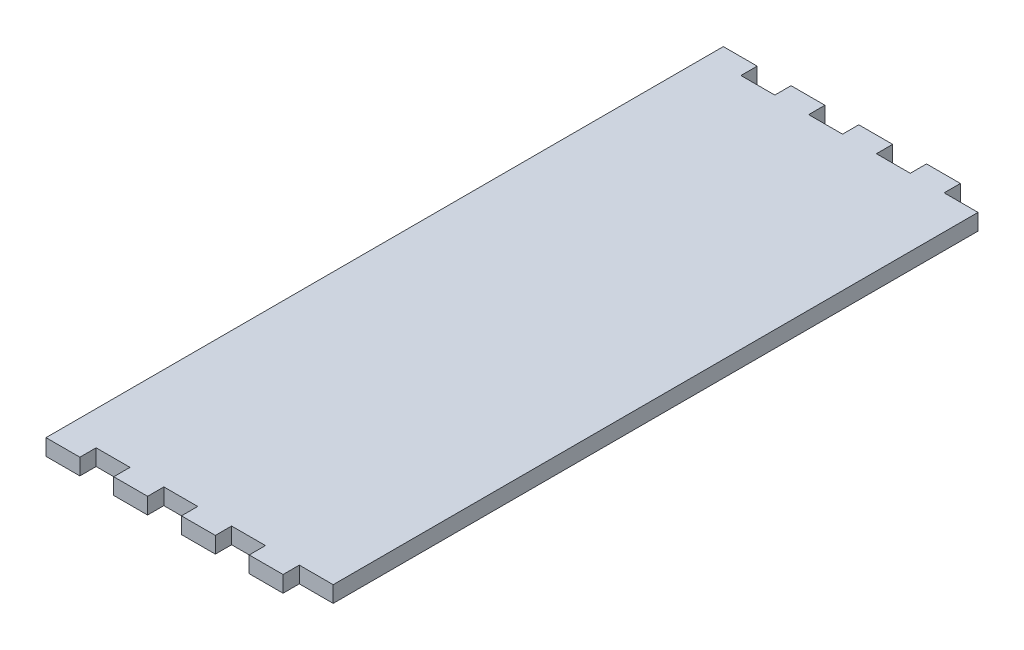
SolidWorks part; units mm, degrees
ref_plane "Front Plane" through (0, 0, 0) normal (0, 0, 1) x (1, 0, 0)
ref_plane "Top Plane" through (0, 0, 0) normal (0, 1, 0) x (1, 0, 0)
ref_plane "Right Plane" through (0, 0, 0) normal (1, 0, 0) x (0, 0, -1)
sketch "Sketch1" plane through (0, 0, 0) normal (0, 1, 0) x (1, 0, 0)
  line L0 (0, 0) -> (6.35, 0)
  line L1 (0, -127) -> (50.8, -127)
  line L2 (0, -127) -> (0, 0)
  line L3 (0, 0) -> (50.8, 0)
  line L4 (50.8, -127) -> (50.8, 0)
  line L5 (6.35, 0) -> (6.35, -3.048)
  line L6 (6.35, -3.048) -> (12.7, -3.048)
  line L7 (12.7, -3.048) -> (12.7, 0)
  line L8 (12.7, 0) -> (19.05, 0)
  line L9 (19.05, 0) -> (19.05, -3.048)
  line L10 (19.05, -3.048) -> (25.4, -3.048)
  line L11 (25.4, -3.048) -> (25.4, 0)
  line L12 (25.4, 0) -> (31.75, 0)
  line L13 (31.75, 0) -> (31.75, -3.048)
  line L14 (31.75, -3.048) -> (38.1, -3.048)
  line L15 (38.1, -3.048) -> (38.1, 0)
  line L16 (38.1, 0) -> (44.45, 0)
  line L17 (44.45, 0) -> (44.45, -3.048)
  line L18 (44.45, -3.048) -> (50.8, -3.048)
  line L19 (50.8, -3.048) -> (50.8, 0)
  line L20 (0, -63.5) -> (50.8, -63.5) construction
  line L21 (50.8, -123.952) -> (50.8, -127)
  line L22 (44.45, -123.952) -> (50.8, -123.952)
  line L23 (44.45, -127) -> (44.45, -123.952)
  line L24 (38.1, -127) -> (44.45, -127)
  line L25 (38.1, -123.952) -> (38.1, -127)
  line L26 (31.75, -123.952) -> (38.1, -123.952)
  line L27 (31.75, -127) -> (31.75, -123.952)
  line L28 (25.4, -127) -> (31.75, -127)
  line L29 (25.4, -123.952) -> (25.4, -127)
  line L30 (19.05, -123.952) -> (25.4, -123.952)
  line L31 (19.05, -127) -> (19.05, -123.952)
  line L32 (12.7, -127) -> (19.05, -127)
  line L33 (12.7, -123.952) -> (12.7, -127)
  line L34 (6.35, -123.952) -> (12.7, -123.952)
  line L35 (0, -127) -> (6.35, -127)
  line L36 (6.35, -127) -> (6.35, -123.952)
  point P1 (-0.0305, -67.3432)
  point P37 (24.4003, -53.819)
  point P38 (0, 0)
  point P39 (0, 0)
  dimension "D1" = 127
  dimension "D3" = 3.048
  dimension "D4" = 6.35
  dimension "D5" = 6.35
  dimension "D6" = 4
extrude "Boss-Extrude1" add sketch "Sketch1" along normal blind 3.048 contours L2 L20 L4 L18 L17 L3 L15 L14 L13 L11 L10 L9 L7 L6 L5 L0 | L20 L2 L1 L36 L34 L33 L31 L30 L29 L27 L26 L25 L23 L22 L4
